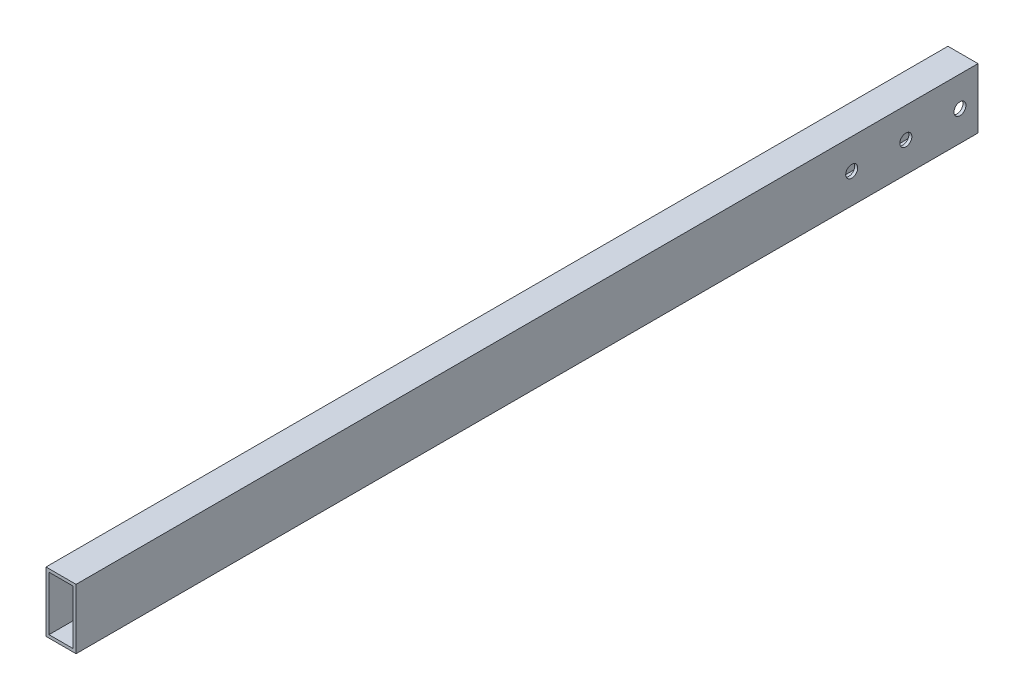
SolidWorks part; units mm, degrees
ref_plane "Front Plane" through (0, 0, 0) normal (0, 0, 1) x (1, 0, 0)
ref_plane "Top Plane" through (0, 0, 0) normal (0, 1, 0) x (1, 0, 0)
ref_plane "Right Plane" through (0, 0, 0) normal (1, 0, 0) x (0, 0, -1)
sketch "Sketch1" plane through (0, 0, 0) normal (0, 0, 1) x (1, 0, 0)
  line L0 (-4, 9) -> (4, 9)
  line L1 (-5, -10) -> (5, -10)
  line L2 (-5, -10) -> (-5, 10)
  line L3 (-5, 10) -> (5, 10)
  line L4 (5, -10) -> (5, 10)
  line L5 (-5, -10) -> (5, 10) construction
  line L6 (-5, 10) -> (5, -10) construction
  line L7 (4, -9) -> (4, 9)
  line L8 (-4, -9) -> (4, -9)
  line L9 (-4, -9) -> (-4, 9)
  point P0 (0, 0)
  dimension "D2" = 10
  dimension "D3" = 20
  dimension "D1" = 1
extrude "Boss-Extrude1" add sketch "Sketch1" along normal blind 300
sketch "Sketch2" plane through (5, 0, 0) normal (1, 0, 0) x (0, 0, -1)
  line L0 (0, 0) -> (-300, 0) construction
  line L1 (0, -10) -> (0, 10) construction
  line L2 (-300, -10) -> (-300, 10) construction
  circle A0 centre (-6, 0) radius 2
  circle A1 centre (-24, 0) radius 2
  circle A2 centre (-42, 0) radius 2
  dimension "D1" = 4
  dimension "D2" = 18
  dimension "D3" = 18
  dimension "D4" = 6
extrude "Cut-Extrude1" cut sketch "Sketch2" against normal up to next
